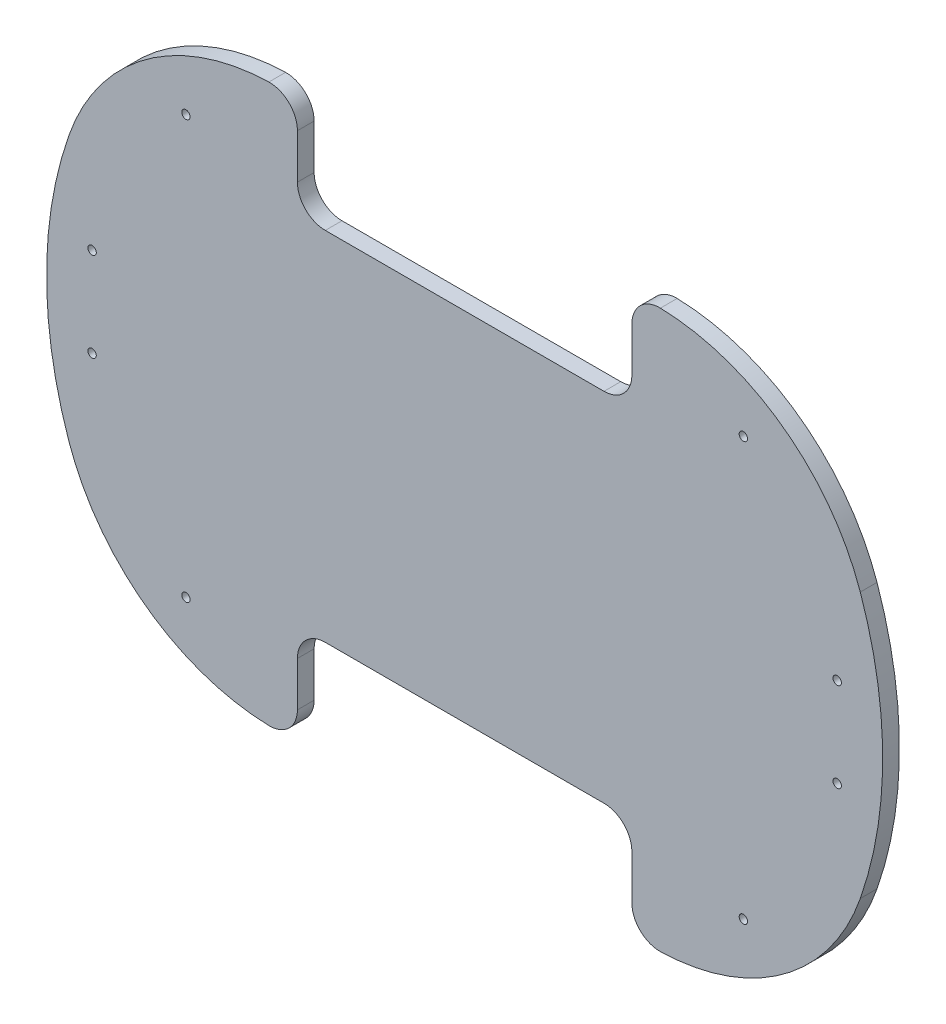
SolidWorks part; units mm, degrees
ref_plane "Front Plane" through (0, 0, 0) normal (0, 0, 1) x (1, 0, 0)
ref_plane "Top Plane" through (0, 0, 0) normal (0, 1, 0) x (1, 0, 0)
ref_plane "Right Plane" through (0, 0, 0) normal (1, 0, 0) x (0, 0, -1)
sketch "Sketch1" plane through (0, 0, 0) normal (0, 0, 1) x (1, 0, 0)
  line L0 (0, 32) -> (0, -32) construction
  line L1 (-55, 50) -> (-30, 50)
  line L2 (-55, 50) -> (-55, -50)
  line L3 (-55, -50) -> (-30, -50)
  line L4 (55, 50) -> (55, -50)
  line L5 (-55, 50) -> (55, -50) construction
  line L6 (-55, -50) -> (55, 50) construction
  line L7 (-55, 50) -> (-55, -50)
  line L8 (-30, 50) -> (-30, 32)
  line L9 (-30, 32) -> (30, 32)
  line L10 (30, 32) -> (30, 50)
  line L12 (-55, 0) -> (55, 0) construction
  line L13 (-30, -50) -> (-30, -32)
  line L14 (-30, -32) -> (30, -32)
  line L15 (30, -32) -> (30, -50)
  line L17 (30, 50) -> (55, 50)
  line L18 (30, -50) -> (55, -50)
  arc A0 (55, 50) -> (55, -50) centre (2.5, 0) cw
  arc A1 (-55, 50) -> (-55, -50) centre (-2.5, 0) ccw
  point P0 (0, 0)
  point P7 (75, 0)
  point P8 (55, 0)
  dimension "D1" = 110
  dimension "D2" = 100
  dimension "D3" = 20
  dimension "D4" = 25
  dimension "D5" = 25
  dimension "D6" = 18
extrude "Boss-Extrude1" add sketch "Sketch1" along normal blind 3 contours L2 A1 | L4 L1 L2 L3 | A0 L4
fillet "Fillet1" radius 39 4 edges at (-55, -50, 1.5) (-55, 50, 1.5) (55, -50, 1.5) (55, 50, 1.5)
fillet "Fillet3" radius 5 8 edges at (30, -50, 1.5) (-30, -50, 1.5) (30, 50, 1.5) (-30, 50, 1.5) (30, 32, 1.5) (-30, 32, 1.5) (-30, -32, 1.5) (30, -32, 1.5)
sketch "Sketch7" plane through (0, 0, 3) normal (0, 0, 1) x (1, 0, 0)
  line L1 (-50, 37.5) -> (50, 37.5) construction
  line L2 (-50, 37.5) -> (-50, -37.5) construction
  line L3 (-50, -37.5) -> (50, -37.5) construction
  line L4 (50, 37.5) -> (50, -37.5) construction
  line L5 (-50, 37.5) -> (50, -37.5) construction
  line L6 (-50, -37.5) -> (50, 37.5) construction
  circle A0 centre (-50, 37.5) radius 0.75
  circle A1 centre (-50, -37.5) radius 0.75
  circle A2 centre (50, -37.5) radius 0.75
  circle A3 centre (50, 37.5) radius 0.75
  point P0 (0, 0)
  dimension "D3" = 1.5
  dimension "D4" = 1.5
  dimension "D5" = 1.5
  dimension "D6" = 1.5
  dimension "D1" = 100
  dimension "D2" = 75
extrude "Cut-Extrude2" cut sketch "Sketch7" against normal blind 3
sketch "Sketch8" plane through (0, 0, 3) normal (0, 0, 1) x (1, 0, 0)
  line L0 (-66.831, 32.2712) -> (-66.831, -32.2712) construction
  line L1 (0, 32) -> (0, -32) construction
  line L2 (-25, 32) -> (25, 32) construction
  line L3 (-25, -32) -> (25, -32) construction
  arc A0 (-35.1261, 49.9876) -> (-70.9801, 23.806) centre (-34.1425, 11) ccw construction
  arc A1 (-70.9801, -23.806) -> (-35.1261, -49.9876) centre (-34.1425, -11) ccw construction
  circle A2 centre (-66.831, 8) radius 0.75
  circle A3 centre (-66.831, -8) radius 0.75
  circle A4 centre (66.831, -8) radius 0.75
  circle A5 centre (66.831, 8) radius 0.75
  point P12 (-66.831, 0)
  dimension "D1" = 1.5
  dimension "D2" = 1.5
  dimension "D3" = 8
  dimension "D4" = 8
extrude "Cut-Extrude3" cut sketch "Sketch8" against normal through all
